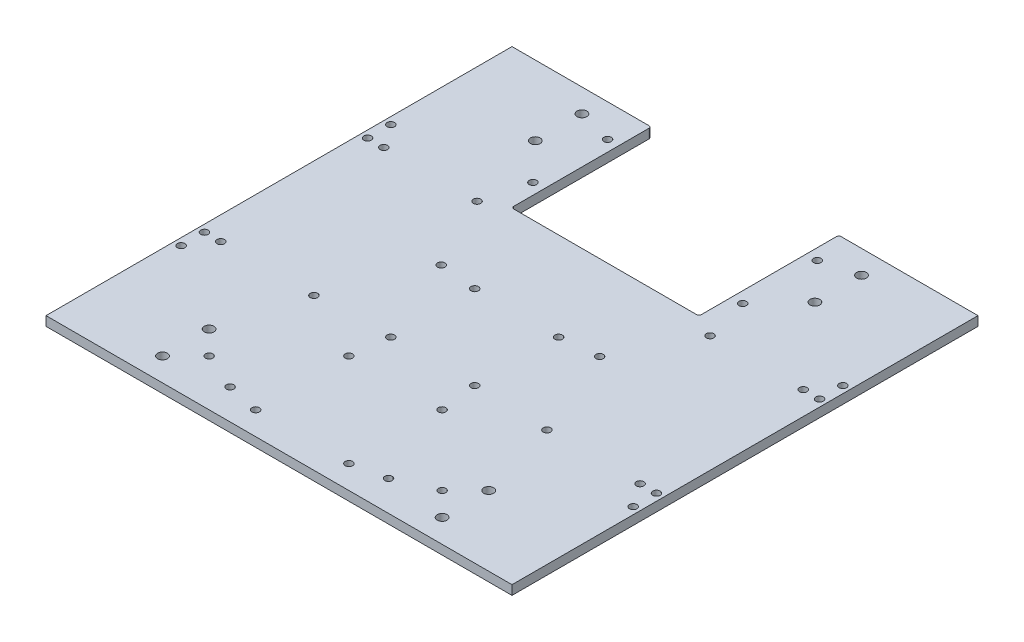
SolidWorks part; units mm, degrees
material "6061 合金"
ref_plane "前视基准面" through (0, 0, 0) normal (0, 0, 1) x (1, 0, 0)
ref_plane "上视基准面" through (0, 0, 0) normal (0, 1, 0) x (1, 0, 0)
ref_plane "右视基准面" through (0, 0, 0) normal (1, 0, 0) x (0, 0, -1)
sketch "草图1" plane through (0, 0, 0) normal (0, 1, 0) x (1, 0, 0)
  line L0 (-100, 0) -> (0, 0) construction
  line L1 (-100, -100) -> (100, -100)
  line L2 (-100, -100) -> (-100, 100)
  line L3 (-100, 100) -> (100, 100)
  line L4 (100, -100) -> (100, 100)
  line L5 (-100, -100) -> (100, 100) construction
  line L6 (-100, 100) -> (100, -100) construction
  line L7 (0, 100) -> (0, 0) construction
  circle A0 centre (-97, 35) radius 1.6
  circle A1 centre (-97, 45) radius 1.6
  circle A2 centre (-97, -45) radius 1.6
  circle A3 centre (-97, -35) radius 1.6
  circle A4 centre (97, -45) radius 1.6
  circle A5 centre (97, -35) radius 1.6
  circle A6 centre (97, 35) radius 1.6
  circle A7 centre (97, 45) radius 1.6
  circle A8 centre (-18, -34) radius 1.6
  circle A9 centre (18, -34) radius 1.6
  circle A10 centre (18, 2) radius 1.6
  circle A11 centre (-18, 2) radius 1.6
  circle A16 centre (-34, -87) radius 1.6
  circle A17 centre (34, -87) radius 1.6
  circle A18 centre (34, 3.6) radius 1.6
  circle A19 centre (-34, 3.6) radius 1.6
  circle A20 centre (-60, 90) radius 2.1
  circle A21 centre (-60, 70) radius 2.1
  circle A22 centre (60, 70) radius 2.1
  circle A23 centre (60, 90) radius 2.1
  circle A24 centre (60, -70) radius 2.1
  circle A25 centre (60, -90) radius 2.1
  circle A26 centre (-60, -70) radius 2.1
  circle A27 centre (-60, -90) radius 2.1
  circle A28 centre (-90, 35) radius 1.6
  circle A29 centre (-50, 35) radius 1.6
  circle A30 centre (-50, -35) radius 1.6
  circle A31 centre (-90, -35) radius 1.6
  circle A32 centre (90, 35) radius 1.6
  circle A33 centre (50, 35) radius 1.6
  circle A34 centre (50, -35) radius 1.6
  circle A35 centre (90, -35) radius 1.6
  circle A36 centre (-20, -50) radius 1.6
  circle A37 centre (20, -50) radius 1.6
  circle A38 centre (20, -90) radius 1.6
  circle A39 centre (-20, -90) radius 1.6
  point P0 (0, 0)
  point P27 (0, 54)
  dimension "D3" = 3.2
  dimension "D4" = 35
  dimension "D5" = 3
  dimension "D7" = 3.2
  dimension "D8" = 34
  dimension "D12" = 3.2
  dimension "D13" = 35
  dimension "D14" = 10
  dimension "D17" = 3.2
  dimension "D18" = 87
  dimension "D19" = 34
  dimension "D22" = 4.2
  dimension "D23" = 10
  dimension "D24" = 60
  dimension "D26" = 3.2
  dimension "D27" = 20
  dimension "D28" = 50
  dimension "D1" = 200
  dimension "D2" = 200
  dimension "D9" = 18
  dimension "D6" = 2
  dimension "D10" = 2
  dimension "D11" = 2
  dimension "D20" = 2
  dimension "D21" = 2
  dimension "D25" = 2
  dimension "D15" = 2
  dimension "D16" = 2
  dimension "D29" = 2
  dimension "D30" = 2
extrude "凸台-拉伸1" add sketch "草图1" along normal blind 4
sketch "草图2" plane through (0, 4, 0) normal (0, 1, 0) x (1, 0, 0)
  line L0 (0, 100) -> (0, -100) construction
  line L1 (100, 100) -> (-100, 100) construction
  line L2 (-100, -100) -> (100, -100) construction
  line L3 (40.25, 70) -> (-40.25, 70) construction
  line L4 (-40.25, 40) -> (40.25, 40)
  line L5 (-40.25, 40) -> (-40.25, 100)
  line L6 (-40.25, 100) -> (40.25, 100)
  line L7 (40.25, 40) -> (40.25, 100)
  line L8 (-40.25, 40) -> (40.25, 100) construction
  line L9 (-40.25, 100) -> (40.25, 40) construction
  circle A0 centre (45, 86) radius 1.6
  circle A1 centre (45, 54) radius 1.6
  circle A2 centre (-45, 54) radius 1.6
  circle A3 centre (-45, 86) radius 1.6
  point P6 (0, 70)
  dimension "D4" = 3.2
  dimension "D5" = 16
  dimension "D6" = 45
  dimension "D1" = 60
  dimension "D2" = 80.5
  dimension "D3" = 0
extrude "切除-拉伸1" cut sketch "草图2" against normal up to next
sketch "草图3" plane through (0, 4, 0) normal (0, 1, 0) x (1, 0, 0)
  line L0 (0, 40) -> (0, -100) construction
  line L1 (-40.25, 40) -> (40.25, 40) construction
  line L2 (-100, -100) -> (100, -100) construction
  circle A0 centre (-50, -80) radius 1.6
  circle A1 centre (50, -80) radius 1.6
  circle A2 centre (50, 35) radius 1.6
  circle A3 centre (-50, 35) radius 1.6
  dimension "D1" = 3.2
  dimension "D2" = 20
  dimension "D3" = 50
  dimension "D4" = 2
  dimension "D5" = 2
extrude "切除-拉伸2" cut sketch "草图3" against normal up to next (4 mm away)
fillet "圆角1" radius 1 4 edges at (40.25, 2, -100) (40.25, 2, -40) (-40.25, 2, -40) (-40.25, 2, -100)
